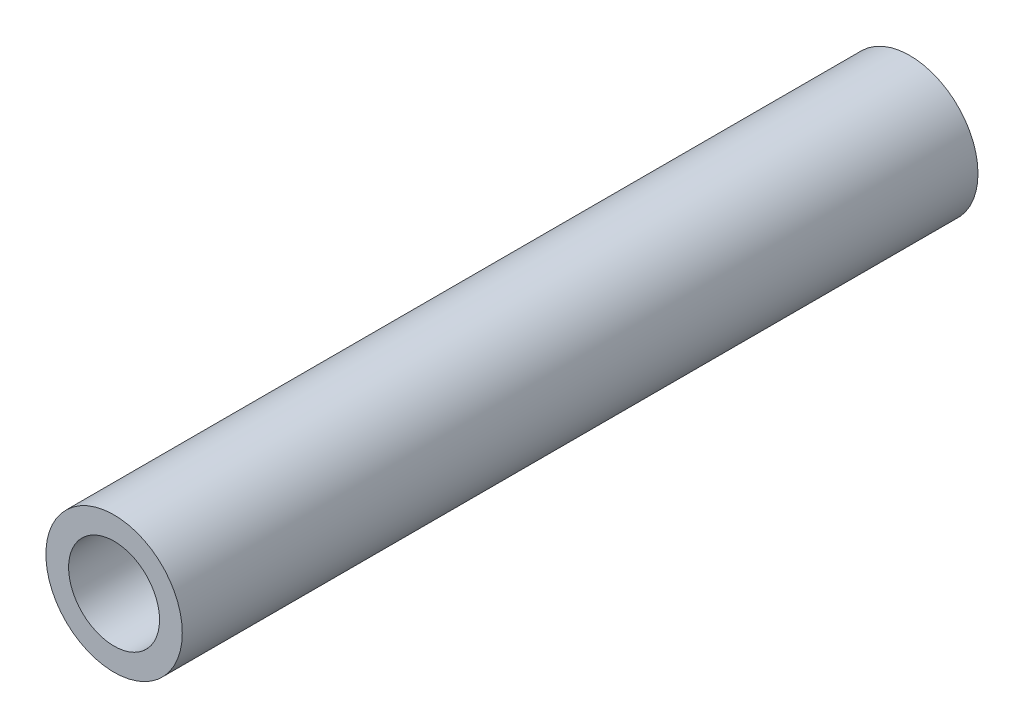
SolidWorks part; units mm, degrees
material "C-Fibra di vetro"
ref_plane "Piano frontale" through (0, 0, 0) normal (0, 0, 1) x (1, 0, 0)
ref_plane "Piano superiore" through (0, 0, 0) normal (0, 1, 0) x (1, 0, 0)
ref_plane "Piano destro" through (0, 0, 0) normal (1, 0, 0) x (0, 0, -1)
sketch "Schizzo1" plane through (0, 0, 0) normal (0, 0, 1) x (1, 0, 0)
  circle A0 centre (215, -26.4239) radius 3
  circle A1 centre (215, -26.4239) radius 2
  dimension "D1" = 1
  dimension "D2" = 6
extrude "Estrusione-Estrusione1" add sketch "Schizzo1" along normal up to surface (35 mm away)
